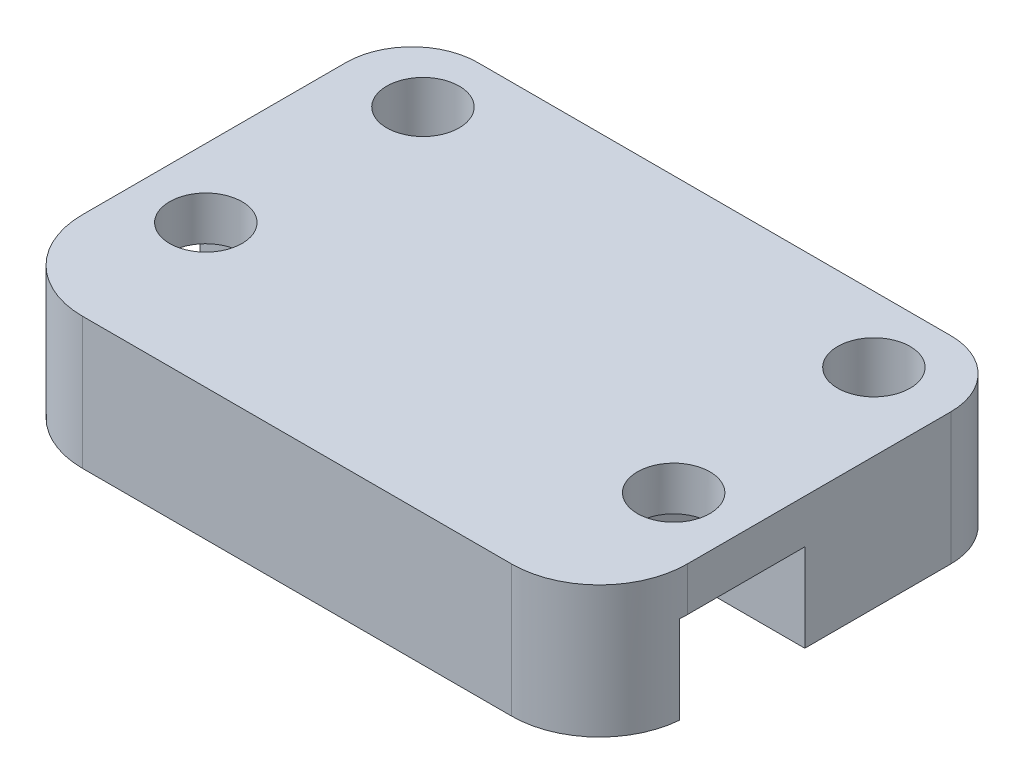
SolidWorks part; units mm, degrees
ref_plane "Front Plane" through (0, 0, 0) normal (0, 0, 1) x (1, 0, 0)
ref_plane "Top Plane" through (0, 0, 0) normal (0, 1, 0) x (1, 0, 0)
ref_plane "Right Plane" through (0, 0, 0) normal (1, 0, 0) x (0, 0, -1)
sketch "Sketch1" plane through (0, 0, 0) normal (0, 0, 1) x (1, 0, 0)
  line L0 (0, 4) -> (0, 0) construction
  line L1 (-13.77, -3) -> (13.77, -3)
  line L2 (-13.77, -3) -> (-13.77, 3)
  line L3 (-13.77, 3) -> (13.77, 3)
  line L4 (13.77, -3) -> (13.77, 3)
  line L5 (-13.77, -3) -> (13.77, 3) construction
  line L6 (-13.77, 3) -> (13.77, -3) construction
  circle A0 centre (0, 4) radius 7.6 construction
  point P0 (0, 0)
  dimension "D3" = 15.2
  dimension "D1" = 7
  dimension "D2" = 1
  dimension "D4" = 27.54
extrude "Boss-Extrude1" add sketch "Sketch1" along normal blind 13 contours A0 L3 L2 L1 L4
sketch "Sketch2" plane through (0, 3, 0) normal (0, 1, 0) x (1, 0, 0)
  line L0 (13.77, 0) -> (7.53, -13) construction
  line L1 (-13.77, 0) -> (-7.53, -13) construction
  line L2 (-13.77, -13) -> (13.77, -13) construction
  line L3 (-13.77, -13) -> (-7.53, -13) construction
  line L4 (7.53, -13) -> (13.77, -13) construction
  line L5 (13.77, -13) -> (13.77, 0) construction
  circle A0 centre (-10.65, -6.5) radius 1.65
  circle A1 centre (10.65, -6.5) radius 1.65
  dimension "D1" = 3.3
  dimension "D2" = 3.12
extrude "Cut-Extrude1" cut sketch "Sketch2" against normal through all
sketch "Sketch4" plane through (0, 0, 0) normal (0, 0, -1) x (-1, 0, 0)
  line L8 (-13.77, -3) -> (13.77, -3)
  line L9 (13.77, -3) -> (13.77, 3)
  line L10 (13.77, 3) -> (-13.77, 3)
  line L11 (-13.77, 3) -> (-13.77, -3)
  line L12 (-13.77, -3) -> (13.77, -3)
  line L13 (13.77, -3) -> (13.77, 3)
  line L14 (13.77, 3) -> (-13.77, 3)
  line L15 (-13.77, 3) -> (-13.77, -3)
  dimension "D1" = 0
extrude "Boss-Extrude2" add sketch "Sketch4" along normal blind 6
sketch "Sketch3" plane through (0, -3, 0) normal (0, -1, 0) x (1, 0, 0)
  line L0 (10.265, -3) -> (-10.265, -3) construction
  line L1 (13.77, -6) -> (-13.77, -6) construction
  line L3 (0, -3) -> (0, 0) construction
  arc A2 (9.4529, 1.5809) -> (12.4155, 1.1255) centre (10.265, -3) ccw construction
  arc A3 (-11.6158, 1) -> (-8.8211, 0.9674) centre (-10.265, -3) ccw construction
  circle A4 centre (10.265, -3) radius 1.65
  circle A5 centre (-10.265, -3) radius 1.65
  dimension "D1" = 3.3
  dimension "D2" = 20.53
  dimension "D3" = 3
fillet "Fillet1" radius 4 2 edges at (13.77, 0, 13) (-13.77, 0, 13)
fillet "Fillet2" radius 3 2 edges at (13.77, 0, -6) (-13.77, 0, -6)
extrude "Cut-Extrude2" cut sketch "Sketch3" against normal through all both and the other way through all
sketch "Sketch6" plane through (0, -3, 0) normal (0, -1, 0) x (1, 0, 0)
  line L0 (12.2954, 9.35) -> (15.2954, 9.35)
  line L1 (13.9409, 6.5) -> (12.2954, 9.35) construction
  line L2 (12.2954, 9.35) -> (9.0046, 9.35)
  line L3 (9.0046, 9.35) -> (7.3591, 6.5)
  line L4 (7.3591, 6.5) -> (9.0046, 3.65)
  line L5 (9.0046, 3.65) -> (12.2954, 3.65)
  line L6 (12.2954, 3.65) -> (13.9409, 6.5) construction
  line L7 (-13.9409, 6.5) -> (-12.2954, 3.65) construction
  line L8 (-12.2954, 3.65) -> (-9.0046, 3.65)
  line L9 (-9.0046, 3.65) -> (-7.3591, 6.5)
  line L10 (-7.3591, 6.5) -> (-9.0046, 9.35)
  line L11 (-9.0046, 9.35) -> (-12.2954, 9.35)
  line L12 (-12.2954, 9.35) -> (-13.9409, 6.5) construction
  line L13 (15.2954, 9.35) -> (15.2954, 3.65)
  line L14 (15.2954, 3.65) -> (12.2954, 3.65)
  line L15 (-12.2954, 9.35) -> (-15.2954, 9.35)
  line L16 (-15.2954, 9.35) -> (-15.2954, 3.65)
  line L17 (-15.2954, 3.65) -> (-12.2954, 3.65)
  circle A1 centre (10.65, 6.5) radius 2.85 construction
  circle A2 centre (-10.65, 6.5) radius 2.85 construction
  dimension "D1" = 5.7
  dimension "D2" = 3
extrude "Cut-Extrude3" cut sketch "Sketch6" against normal blind 4
